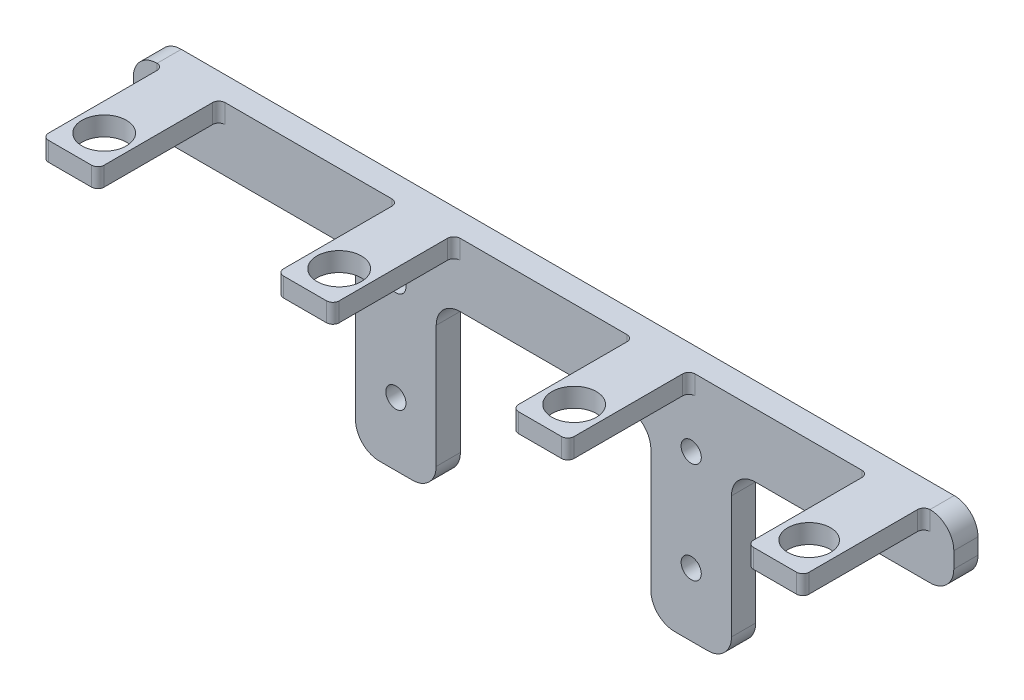
SolidWorks part; units mm, degrees
ref_plane "Front Plane" through (0, 0, 0) normal (0, 0, 1) x (1, 0, 0)
ref_plane "Top Plane" through (0, 0, 0) normal (0, 1, 0) x (1, 0, 0)
ref_plane "Right Plane" through (0, 0, 0) normal (1, 0, 0) x (0, 0, -1)
sketch "Sketch1" plane through (0, 0, 0) normal (0, 0, 1) x (1, 0, 0)
  line L0 (0, -120.5539) -> (0, 89.72) construction
  line L2 (-95.4, 59.77) -> (-95.4, 79.77)
  line L3 (-95.4, 79.77) -> (163, 79.77)
  line L4 (163, 59.77) -> (163, 79.77)
  line L6 (0, 59.77) -> (0, 6.27)
  line L7 (0, 6.27) -> (-25.4, 6.27)
  line L8 (-25.4, 59.77) -> (-25.4, 6.27)
  line L9 (-95.4, 59.77) -> (-25.4, 59.77)
  line L10 (0, 33.02) -> (-25.4, 33.02) construction
  line L11 (67.6, -120.5539) -> (67.6, 89.72) construction
  line L13 (93, 59.77) -> (93, 6.27)
  line L14 (93, 6.27) -> (67.6, 6.27)
  line L15 (67.6, 59.77) -> (67.6, 6.27)
  line L16 (0, 59.77) -> (67.6, 59.77)
  line L17 (93, 33.02) -> (67.6, 33.02) construction
  line L18 (-25.4, -120.5539) -> (-25.4, 89.72) construction
  line L19 (93, -120.5539) -> (93, 89.72) construction
  line L20 (93, 59.77) -> (163, 59.77)
  line L21 (0, 6.27) -> (0, 0) construction
  point P20 (-12.7, 64.77)
  point P21 (80.3, 33.02)
  point P22 (-12.7, 33.02)
  point P230 (80.3, 33.02)
  point P324 (-12.7, 33.02)
  dimension "D1" = 20
  dimension "D2" = 163
  dimension "D3" = 6.27
  dimension "D4" = 64.77
extrude "Boss-Extrude1" add sketch "Sketch1" along normal blind 7.62
sketch "Sketch2" plane through (0, 0, 0) normal (0, 0, -1) x (-1, 0, 0)
  circle A0 centre (-80.3, 57.97) radius 3.18
  circle A1 centre (-80.3, 26.22) radius 3.18
  circle A2 centre (12.7, 26.22) radius 3.18
  circle A3 centre (12.7, 57.97) radius 3.18
  dimension "D1" = 6.36
extrude "Cut-Extrude1" cut sketch "Sketch2" against normal blind 45.72
sketch "Sketch3" plane through (0, 79.77, 0) normal (0, 1, 0) x (1, 0, 0)
  line L0 (163, -7.62) -> (-95.4, -7.62) construction
  line L1 (153.55, -7.62) -> (136.05, -7.62)
  line L2 (153.55, -7.62) -> (153.55, -45.725)
  line L3 (153.55, -45.725) -> (136.05, -45.725)
  line L4 (136.05, -7.62) -> (136.05, -45.725)
  line L5 (144.8, -45.725) -> (144.8, -7.62) construction
  line L6 (-95.4, -7.62) -> (-95.4, 0) construction
  line L7 (65.5351, -45.7255) -> (154.0508, -45.7224) construction
  line L8 (33.8, 0) -> (33.8, -7.62) construction
  line L9 (163, 0) -> (-95.4, 0) construction
  line L10 (-85.95, -7.62) -> (-68.45, -7.62)
  line L11 (-68.45, -7.62) -> (-68.45, -45.725)
  line L12 (-85.95, -7.62) -> (-85.95, -45.725)
  line L13 (-85.95, -45.725) -> (-68.45, -45.725)
  line L14 (-40.2, -7.62) -> (-40.2, 0) construction
  line L15 (5.55, -7.62) -> (-11.95, -7.62)
  line L16 (5.55, -7.62) -> (5.55, -45.725)
  line L17 (5.55, -45.725) -> (-11.95, -45.725)
  line L18 (-11.95, -7.62) -> (-11.95, -45.725)
  line L19 (107.8, 0) -> (107.8, -7.62) construction
  line L20 (62.05, -7.62) -> (62.05, -45.725)
  line L21 (62.05, -7.62) -> (79.55, -7.62)
  line L22 (79.55, -7.62) -> (79.55, -45.725)
  line L23 (62.05, -45.725) -> (79.55, -45.725)
  arc A0 (151.0507, -41.0962) -> (153.5504, -34.9724) centre (144.8004, -34.9727) ccw construction
  arc A1 (136.054, -35.223) -> (136.6765, -38.223) centre (144.8004, -34.9727) ccw construction
  dimension "D1" = 55.2
  dimension "D4" = 157.45
extrude "Boss-Extrude2" add sketch "Sketch3" against normal blind 5.9995
fillet "Fillet1" radius 7.5 12 edges at (-25.4, 6.27, 3.81) (0, 6.27, 3.81) (163, 79.77, 3.81) (163, 59.77, 3.81) (67.6, 6.27, 3.81) (93, 6.27, 3.81) (93, 59.77, 3.81) (-25.4, 59.77, 3.81) (67.6, 59.77, 3.81) (0, 59.77, 3.81) (-95.4, 79.77, 3.81) (-95.4, 59.77, 3.81)
sketch "Sketch5" plane through (0, 79.77, 0) normal (0, 1, 0) x (1, 0, 0)
  circle A0 centre (144.8004, -34.9727) radius 6.75
  circle A1 centre (70.8004, -34.9753) radius 7
  circle A2 centre (-3.1996, -34.9779) radius 7
  circle A3 centre (-77.1996, -34.9805) radius 7
  dimension "D1" = 13.5
  dimension "D2" = 14
  dimension "D3" = 14
  dimension "D4" = 14
extrude "Cut-Extrude2" cut sketch "Sketch5" against normal blind 10
fillet "Fillet2" radius 2 16 edges at (-85.95, 76.7703, 7.62) (-68.45, 76.7703, 7.62) (-85.95, 76.7703, 45.725) (-68.45, 76.7703, 45.725) (5.55, 76.7703, 7.62) (-11.95, 76.7703, 7.62) (-11.95, 76.7703, 45.725) (5.55, 76.7703, 45.725) (62.05, 76.7703, 7.62) (79.55, 76.7703, 7.62) (62.05, 76.7703, 45.725) (79.55, 76.7703, 45.725) (136.05, 76.7703, 7.62) (136.05, 76.7703, 45.725) (153.55, 76.7703, 45.725) (153.55, 76.7703, 7.62)
